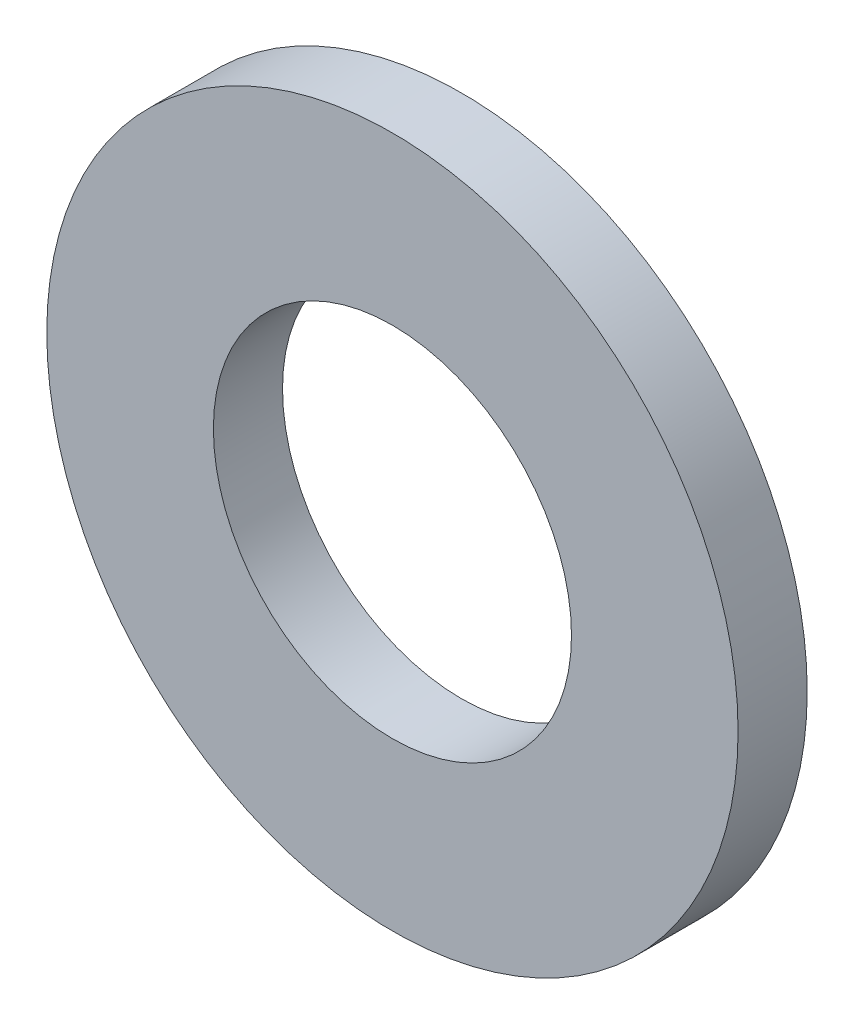
SolidWorks part; units mm, degrees
ref_plane "Front" through (0, 0, 0) normal (0, 0, 1) x (1, 0, 0)
ref_plane "Top" through (0, 0, 0) normal (0, 1, 0) x (1, 0, 0)
ref_plane "Right" through (0, 0, 0) normal (1, 0, 0) x (0, 0, -1)
sketch "Sketch1" plane through (0, 0, 0) normal (0, 0, 1) x (1, 0, 0)
  circle A0 centre (0, 0) radius 2.59
  circle A1 centre (0, 0) radius 5
  dimension "d1" = 5.18
  dimension "d2" = 10
extrude "Base-Extrude" add sketch "Sketch1" against normal blind 1
